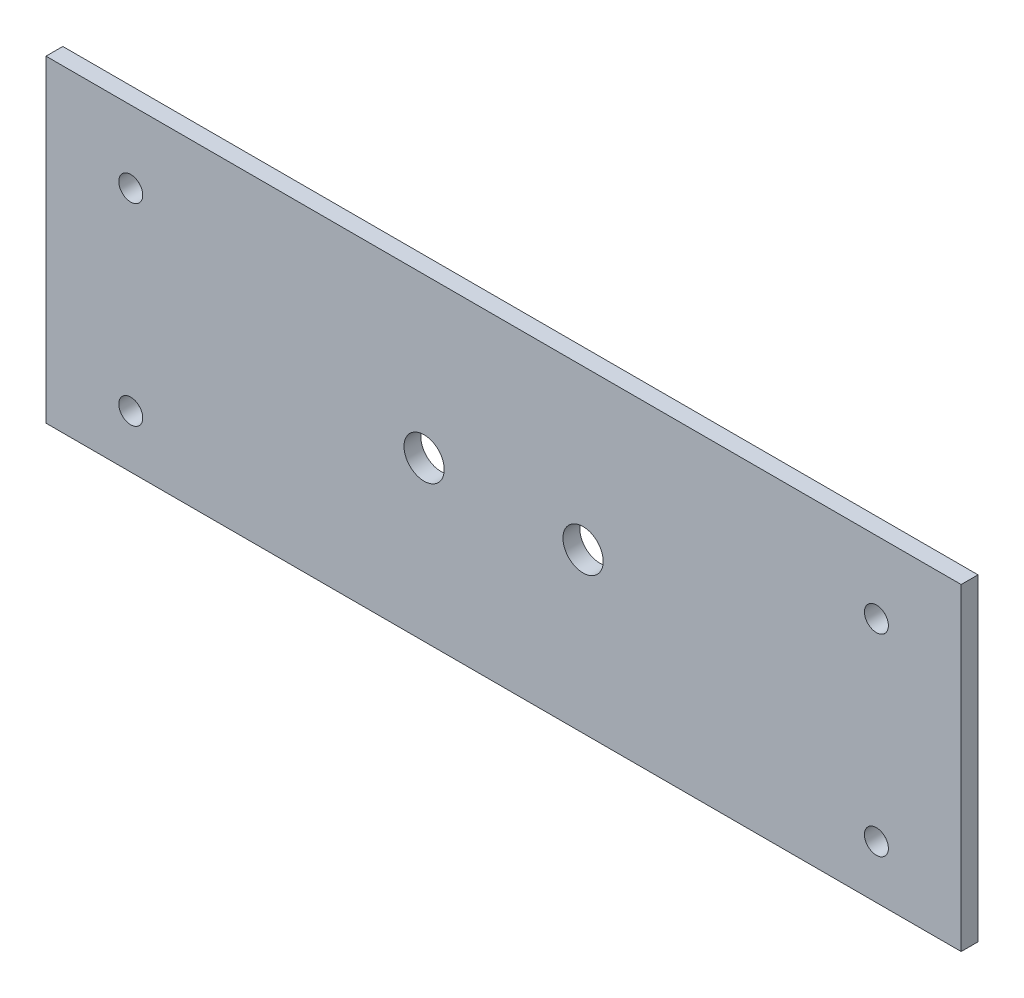
SolidWorks part; units mm, degrees
ref_plane "Front Plane" through (0, 0, 0) normal (0, 0, 1) x (1, 0, 0)
ref_plane "Top Plane" through (0, 0, 0) normal (0, 1, 0) x (1, 0, 0)
ref_plane "Right Plane" through (0, 0, 0) normal (1, 0, 0) x (0, 0, -1)
sketch "Sketch2" plane through (0, 0, 0) normal (0, 0, 1) x (1, 0, 0)
  line L1 (-43.185, 0) -> (43.185, 0)
  line L2 (-43.185, 0) -> (-43.185, 30)
  line L3 (-43.185, 30) -> (43.185, 30)
  line L4 (43.185, 0) -> (43.185, 30)
  dimension "D1" = 86.37
  dimension "D2" = 30
extrude "Boss-Extrude1" add sketch "Sketch2" along normal blind 1.5875
hole_wizard "#1 Clearance Hole1" positions "Sketch4" profile "Sketch3" hole size "#1" standard "ANSI Inch" end condition through all
sketch "Sketch4" plane through (0, 0, 1.5875) normal (0, 0, 1) x (1, 0, 0)
  line L0 (43.185, 0) -> (43.185, 30) construction
  line L1 (0, 0) -> (0, 30) construction
  line L2 (43.185, 30) -> (-43.185, 30) construction
  point P0 (35.185, 23.2)
  point P2 (35.185, 5)
  point P16 (-35.185, 5)
  point P17 (-35.185, 23.2)
  dimension "D1" = 8
  dimension "D2" = 18.2
  dimension "D3" = 5
sketch "Sketch3" plane through (35.185, 23.2, 1.5875) normal (1, 0, 0) x (0, -1, 0)
  line L0 (0, 0) -> (0, 1.5875)
  line L1 (0, 1.5875) -> (1.1303, 1.5875)
  line L2 (1.1303, 1.5875) -> (1.1303, 0)
  line L5 (1.1303, 0) -> (0, 0)
  line L11 (0, -6.35) -> (0, 107.95) construction
  dimension "Thru Hole Dia." = 2.2606
  dimension "Thru Hole Depth" = 1.5875
hole_wizard "#6 Clearance Hole1" positions "Sketch6" profile "Sketch5" hole size "#6" standard "ANSI Inch" end condition through all
sketch "Sketch6" plane through (0, 0, 0) normal (0, 0, -1) x (-1, 0, 0)
  line L1 (0, 0) -> (0, 30) construction
  line L2 (-43.185, 30) -> (43.185, 30) construction
  point P14 (7.5, 15)
  point P20 (-7.5, 15)
  dimension "D1" = 7.5
  dimension "D2" = 15
sketch "Sketch5" plane through (-7.5, 15, 0) normal (1, 0, 0) x (0, 1, 0)
  line L0 (0, 0) -> (0, 1.5875)
  line L1 (0, 1.5875) -> (1.8986, 1.5875)
  line L2 (1.8986, 1.5875) -> (1.8986, 0)
  line L5 (1.8986, 0) -> (0, 0)
  line L11 (0, -6.35) -> (0, 107.95) construction
  dimension "Thru Hole Dia." = 3.7973
  dimension "Thru Hole Depth" = 1.5875
